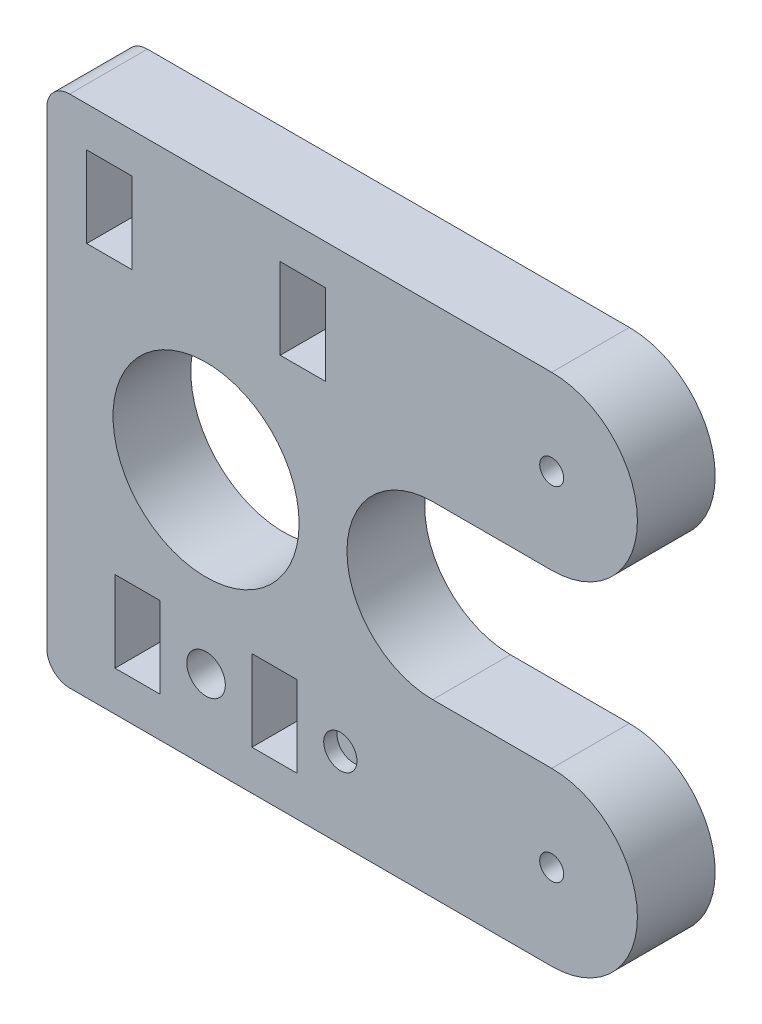
SolidWorks part; units mm, degrees
material "Acrylic (Medium-high impact)"
ref_plane "Front Plane" through (0, 0, 0) normal (0, 0, 1) x (1, 0, 0)
ref_plane "Top Plane" through (0, 0, 0) normal (0, 1, 0) x (1, 0, 0)
ref_plane "Right Plane" through (0, 0, 0) normal (1, 0, 0) x (0, 0, -1)
sketch "Sketch1" plane through (0, 0, 0) normal (0, 0, 1) x (1, 0, 0)
  line L0 (669.2168, 350.1155) -> (648.4638, 350.1155)
  line L1 (646.7465, 348.3982) -> (646.7465, 313.1328)
  line L2 (648.4638, 311.4155) -> (669.2168, 311.4155)
  line L3 (653.1465, 341.0155) -> (653.1465, 347.1155)
  line L4 (653.1465, 347.1155) -> (649.7465, 347.1155)
  line L5 (649.7465, 347.1155) -> (649.7465, 341.0155)
  line L6 (649.7465, 341.0155) -> (653.1465, 341.0155)
  line L7 (651.8765, 314.4155) -> (655.2765, 314.4155)
  line L8 (655.2765, 314.4155) -> (655.2765, 320.5155)
  line L9 (655.2765, 320.5155) -> (651.8765, 320.5155)
  line L10 (651.8765, 320.5155) -> (651.8765, 314.4155)
  line L11 (667.7065, 341.0155) -> (667.7065, 347.1155)
  line L12 (667.7065, 347.1155) -> (664.3065, 347.1155)
  line L13 (664.3065, 347.1155) -> (664.3065, 341.0155)
  line L14 (664.3065, 341.0155) -> (667.7065, 341.0155)
  line L15 (662.1765, 320.5155) -> (662.1765, 314.4155)
  line L16 (662.1765, 314.4155) -> (665.5765, 314.4155)
  line L17 (665.5765, 314.4155) -> (665.5765, 320.5155)
  line L18 (665.5765, 320.5155) -> (662.1765, 320.5155)
  line L19 (-318.4867, 330.7655) -> (49681.5133, 330.7655) construction
  line L21 (653.1465, 341.0155) -> (664.3065, 341.0155) construction
  line L22 (657.2765, 317.4655) -> (655.2765, 317.4655) construction
  line L23 (660.1765, 317.4655) -> (662.1765, 317.4655) construction
  line L24 (658.7265, -665.3806) -> (658.7265, 49334.6194) construction
  line L25 (669.2168, 311.4155) -> (684.7265, 311.4155)
  line L26 (669.2168, 350.1155) -> (684.7265, 350.1155)
  line L27 (684.7265, 317.8655) -> (684.7265, 330.7655) construction
  line L28 (684.7265, 330.7655) -> (684.7265, 343.6655) construction
  line L29 (684.7265, -669.9222) -> (684.7265, 49330.0778) construction
  line L30 (662.1765, 330.7655) -> (662.1765, 350.1155) construction
  line L31 (662.1765, 330.7655) -> (662.1765, 311.4155) construction
  line L32 (684.7265, 337.2155) -> (675.7765, 337.2155)
  line L33 (684.7265, 324.3155) -> (675.7765, 324.3155)
  circle A0 centre (684.7265, 343.6655) radius 0.9
  circle A1 centre (684.7265, 317.8655) radius 0.9
  arc A2 (684.7265, 311.4155) -> (684.7265, 324.3155) centre (684.7265, 317.8655) ccw
  circle A3 centre (658.7265, 317.4655) radius 1.45
  arc A4 (648.4638, 350.1155) -> (646.7465, 348.3982) centre (648.4638, 348.3982) ccw
  arc A5 (684.7265, 350.1155) -> (684.7265, 337.2155) centre (684.7265, 343.6655) cw
  arc A6 (675.7765, 337.2155) -> (675.7765, 324.3155) centre (675.7765, 330.7655) ccw
  arc A7 (646.7465, 313.1328) -> (648.4638, 311.4155) centre (648.4638, 313.1328) ccw
  circle A8 centre (658.7265, 330.7655) radius 7
  point P27 (658.7265, 341.0155)
  point P38 (669.3265, 330.7655)
  point P39 (665.7265, 330.7655)
  dimension "D5" = 2.9
  dimension "D12" = 3.6
  dimension "D13" = 14
  dimension "D14" = 1.8
  dimension "D15" = 1.7173
  dimension "D10" = 26
  dimension "D2" = 6.1
  dimension "D3" = 3.4
  dimension "D4" = 3.4
  dimension "D6" = 6.1
  dimension "D7" = 3
  dimension "D8" = 3
  dimension "D9" = 3
  dimension "D11" = 12.9
  dimension "D16" = 38.7
extrude "Boss-Extrude2" add sketch "Sketch1" along normal blind 5.85
sketch "Sketch2" plane through (0, 0, 5.85) normal (0, 0, 1) x (1, 0, 0)
  line L0 (-341.2735, 317.4655) -> (49658.7265, 317.4655) construction
  line L1 (665.5765, 314.4155) -> (665.5765, 320.5155) construction
  circle A0 centre (668.8265, 317.4655) radius 1.25
  point P5 (667.5765, 317.4655)
  dimension "D1" = 2.5
  dimension "D2" = 2
extrude "Cut-Extrude1" cut sketch "Sketch2" against normal blind 1
